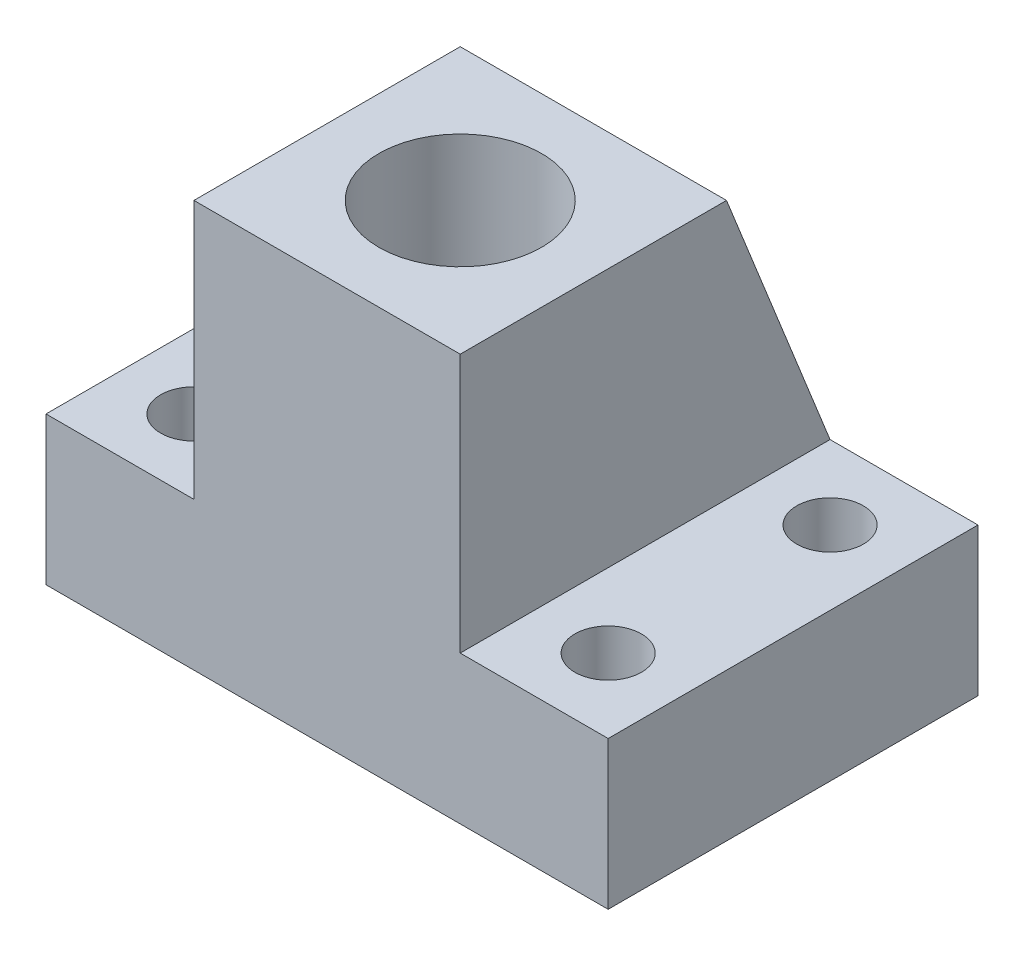
SolidWorks part; units mm, degrees
ref_plane "Alzado" through (0, 0, 0) normal (0, 0, 1) x (1, 0, 0)
ref_plane "Planta" through (0, 0, 0) normal (0, 1, 0) x (1, 0, 0)
ref_plane "Vista lateral" through (0, 0, 0) normal (1, 0, 0) x (0, 0, -1)
sketch "Croquis1" plane through (0, 0, 0) normal (0, 0, 1) x (1, 0, 0)
  line L0 (38, 0) -> (-38, 0)
  line L1 (-38, 0) -> (-38, 20)
  line L2 (-38, 20) -> (-18, 20)
  line L3 (-18, 20) -> (-18, 55)
  line L4 (-18, 55) -> (18, 55)
  line L5 (18, 55) -> (18, 20)
  line L6 (18, 20) -> (38, 20)
  line L7 (38, 20) -> (38, 0)
  dimension "D1" = 18
  dimension "D2" = 18
  dimension "D3" = 20
  dimension "D4" = 20
  dimension "D5" = 20
  dimension "D6" = 35
  dimension "D7" = 20
extrude "Saliente-Extruir1" add sketch "Croquis1" along normal blind 18 and the other way blind 32
sketch "Croquis2" plane through (0, 55, 0) normal (0, 1, 0) x (1, 0, 0)
  circle A0 centre (0, 0) radius 11
  dimension "D1" = 22
extrude "Cortar-Extruir1" cut sketch "Croquis2" against normal blind 30
sketch "Croquis3" plane through (0, 0, 0) normal (0, -1, 0) x (1, 0, 0)
  circle A0 centre (0, 0) radius 11
  dimension "D1" = 22
extrude "Cortar-Extruir2" cut sketch "Croquis3" against normal blind 16
sketch "Croquis4" plane through (0, 25, 0) normal (0, 1, 0) x (1, 0, 0)
  circle A0 centre (0, 0) radius 5.5
  dimension "D1" = 11
extrude "Cortar-Extruir3" cut sketch "Croquis4" against normal up to next
sketch "Croquis5" plane through (18, 0, 0) normal (1, 0, 0) x (0, 0, -1)
  line L0 (32, 55) -> (32, 20)
  line L1 (32, 55) -> (18, 55)
  line L2 (32, 55) -> (-18, 55) construction
  line L3 (18, 55) -> (32, 20)
  dimension "D1" = 36
extrude "Cortar-Extruir4" cut sketch "Croquis5" against normal up to next
sketch "Croquis6" plane through (0, 20, 0) normal (0, 1, 0) x (1, 0, 0)
  line L0 (-38, 32) -> (-38, -18) construction
  line L1 (-18, 32) -> (-38, 32) construction
  line L2 (38, 32) -> (38, -18) construction
  line L3 (38, 32) -> (18, 32) construction
  line L4 (-18, -18) -> (-38, -18) construction
  line L5 (38, -18) -> (18, -18) construction
  circle A0 centre (-28, 22) radius 4.5
  circle A1 centre (-28, -8) radius 4.5
  circle A2 centre (28, 22) radius 4.5
  circle A3 centre (28, -8) radius 4.5
  dimension "D1" = 9
  dimension "D2" = 10
  dimension "D3" = 10
  dimension "D4" = 10
  dimension "D5" = 10
  dimension "D6" = 9
  dimension "D7" = 9
  dimension "D8" = 9
  dimension "D9" = 10
  dimension "D10" = 10
  dimension "D11" = 10
  dimension "D12" = 10
extrude "Cortar-Extruir5" cut sketch "Croquis6" against normal up to next
